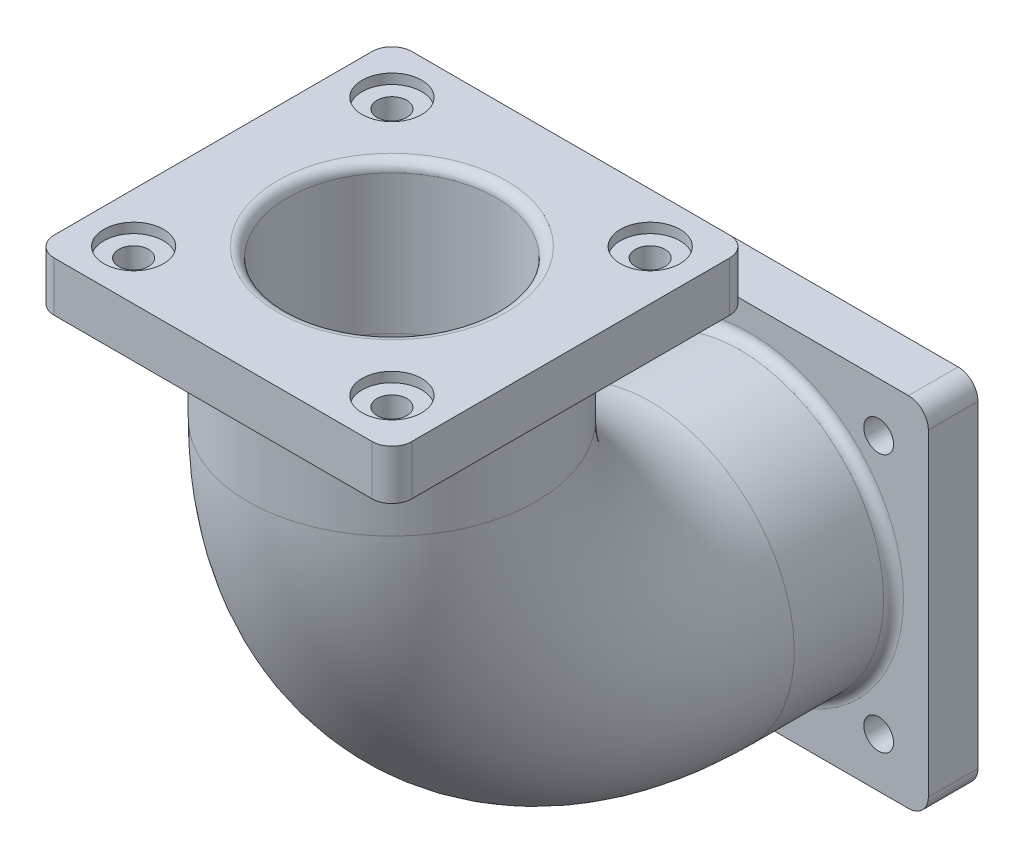
SolidWorks part; units mm, degrees
ref_plane "Front Plane" through (0, 0, 0) normal (0, 0, 1) x (1, 0, 0)
ref_plane "Top Plane" through (0, 0, 0) normal (0, 1, 0) x (1, 0, 0)
ref_plane "Right Plane" through (0, 0, 0) normal (1, 0, 0) x (0, 0, -1)
sketch "Sketch1" plane through (0, 0, 0) normal (0, 0, 1) x (1, 0, 0)
  circle A0 centre (0, 0) radius 145
  circle A1 centre (0, 0) radius 105
  dimension "D1" = 290
  dimension "D2" = 210
sketch "Sketch2" plane through (0, 0, 0) normal (1, 0, 0) x (0, 0, -1)
  line L0 (0, 0) -> (-150, 0)
  line L1 (-410, 260) -> (-410, 410)
  arc A0 (-150, 0) -> (-410, 260) centre (-150, 260) cw
  dimension "D3" = 260
  dimension "D1" = 150
  dimension "D2" = 150
sweep "Sweep1" add profiles "Sketch1" path "Sketch2"
sketch "Sketch3" plane through (0, 0, 0) normal (0, 0, -1) x (-1, 0, 0)
  line L1 (-160, -180) -> (160, -180)
  line L2 (-180, -160) -> (-180, 160)
  line L3 (-160, 180) -> (160, 180)
  line L4 (180, -160) -> (180, 160)
  line L5 (-180, -180) -> (180, 180) construction
  line L6 (-180, 180) -> (180, -180) construction
  arc A0 (-160, -180) -> (-180, -160) centre (-160, -160) cw
  arc A1 (160, -180) -> (180, -160) centre (160, -160) ccw
  arc A2 (160, 180) -> (180, 160) centre (160, 160) cw
  arc A3 (-180, 160) -> (-160, 180) centre (-160, 160) cw
  circle A4 centre (0, 0) radius 105
  point P0 (0, 0)
  dimension "D3" = 20
  dimension "D4" = 210
  dimension "D1" = 360
  dimension "D2" = 360
extrude "Boss-Extrude1" add sketch "Sketch3" against normal blind 50
fillet "Fillet1" radius 10 1 edges at (105, 0, 0)
sketch "Sketch4" plane through (0, 410, 0) normal (0, 1, 0) x (1, 0, 0)
  line L1 (-160, -590) -> (160, -590)
  line L2 (-180, -570) -> (-180, -250)
  line L3 (-160, -230) -> (160, -230)
  line L4 (180, -570) -> (180, -250)
  line L5 (-180, -590) -> (180, -230) construction
  line L6 (-180, -230) -> (180, -590) construction
  circle A0 centre (0, -410) radius 105
  arc A1 (-160, -590) -> (-180, -570) centre (-160, -570) cw
  arc A2 (160, -590) -> (180, -570) centre (160, -570) ccw
  arc A3 (160, -230) -> (180, -250) centre (160, -250) cw
  arc A4 (-180, -250) -> (-160, -230) centre (-160, -250) cw
  point P0 (0, -410)
  dimension "D3" = 210
  dimension "D4" = 20
  dimension "D1" = 360
  dimension "D2" = 360
extrude "Boss-Extrude2" add sketch "Sketch4" against normal blind 50
fillet "Fillet2" radius 10 1 edges at (105, 410, 410)
sketch "Sketch5" plane through (0, 0, 0) normal (0, 0, -1) x (-1, 0, 0)
  line L0 (160, 180) -> (-160, 180) construction
  line L1 (-180, 160) -> (-180, -160) construction
  circle A0 centre (-130, 130) radius 15
  dimension "D1" = 30
  dimension "D2" = 50
  dimension "D3" = 50
extrude "Cut-Extrude1" cut sketch "Sketch5" against normal up to surface (50 mm away) up to face at (145, 0, 50)
sketch "Sketch6" plane through (0, 0, 0) normal (0, 0, -1) x (-1, 0, 0)
  circle A0 centre (-130, 130) radius 30
  dimension "D1" = 60
extrude "Cut-Extrude2" cut sketch "Sketch6" against normal blind 10
pattern_linear "LPattern3" count 2 spacing 260 along (-1, 0, 0) count 2 spacing 260 along (0, -1, 0) of "Cut-Extrude1", "Cut-Extrude2"
fillet "Fillet3" radius 10 1 edges at (145, 0, 50)
sketch "Sketch11" plane through (0, 410, 0) normal (0, 1, 0) x (1, 0, 0)
sketch "Sketch12" plane through (0, 410, 0) normal (0, 1, 0) x (1, 0, 0)
  line L0 (160, -230) -> (-160, -230) construction
  line L1 (-180, -250) -> (-180, -570) construction
  circle A0 centre (-130, -280) radius 15
  dimension "D3" = 30
  dimension "D1" = 50
  dimension "D2" = 50
extrude "Cut-Extrude5" cut sketch "Sketch12" against normal up to surface (50 mm away) up to face at (0, 360, 265)
sketch "Sketch13" plane through (0, 410, 0) normal (0, 1, 0) x (1, 0, 0)
  circle A0 centre (-130, -280) radius 30
  dimension "D1" = 60
extrude "Cut-Extrude6" cut sketch "Sketch13" against normal blind 10
pattern_linear "LPattern5" count 2 spacing 260 along (1, 0, 0) count 2 spacing 260 along (0, 0, 1) of "Cut-Extrude5", "Cut-Extrude6"
fillet "Fillet4" radius 10 1 edges at (0, 360, 265)
